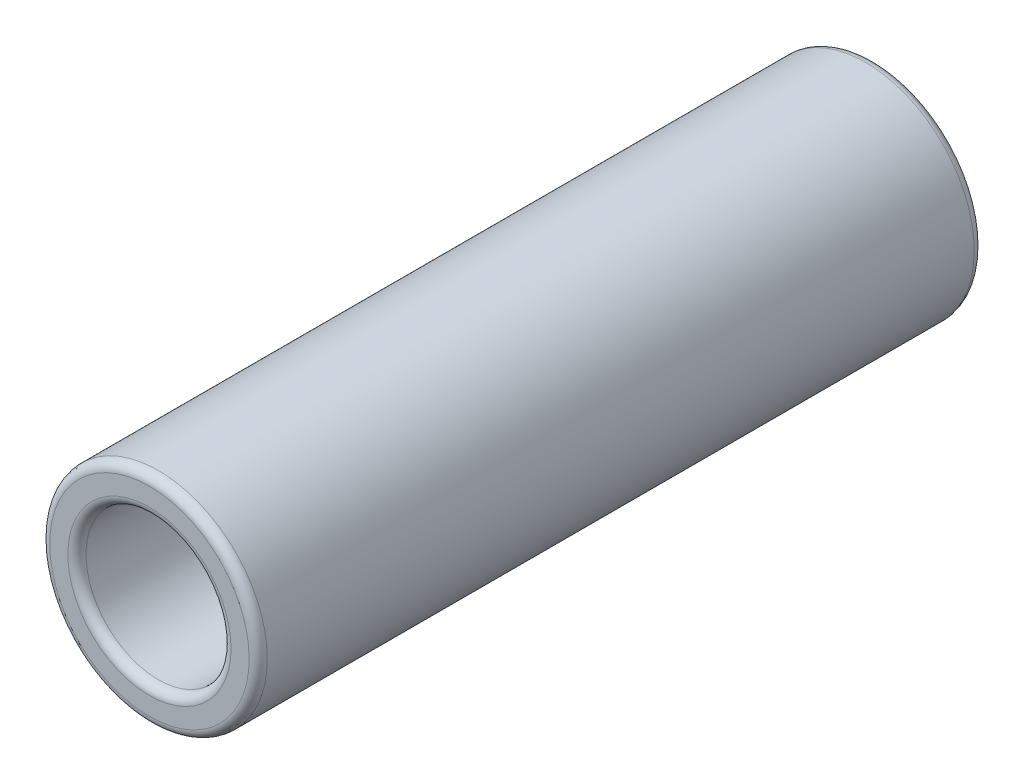
SolidWorks part; units mm, degrees
ref_plane "Front Plane" through (0, 0, 0) normal (0, 0, 1) x (1, 0, 0)
ref_plane "Top Plane" through (0, 0, 0) normal (0, 1, 0) x (1, 0, 0)
ref_plane "Right Plane" through (0, 0, 0) normal (1, 0, 0) x (0, 0, -1)
sketch "Sketch1" plane through (0, 0, 0) normal (0, 0, 1) x (1, 0, 0)
  circle A0 centre (0, 0) radius 4
  circle A1 centre (0, 0) radius 6
  dimension "D1" = 8
  dimension "D2" = 12
extrude "Boss-Extrude1" add sketch "Sketch1" along normal mid plane 40
fillet "Fillet1" radius 0.5 4 edges at (6, 0, -20) (4, 0, -20) (4, 0, 20) (6, 0, 20)
